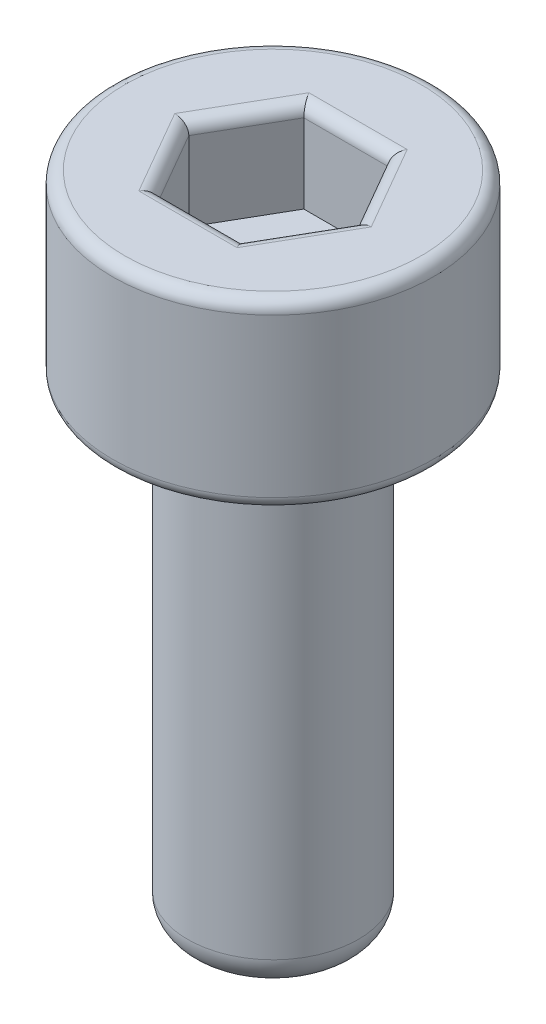
SolidWorks part; units mm, degrees
ref_plane "Front Plane" through (0, 0, 0) normal (0, 0, 1) x (1, 0, 0)
ref_plane "Top Plane" through (0, 0, 0) normal (0, 1, 0) x (1, 0, 0)
ref_plane "Right Plane" through (0, 0, 0) normal (1, 0, 0) x (0, 0, -1)
sketch "Sketch1" plane through (0, 0, 0) normal (0, 1, 0) x (1, 0, 0)
  circle A0 centre (0, 0) radius 2.64
  dimension "D1" = 5.28
extrude "Boss-Extrude1" add sketch "Sketch1" along normal blind 3
sketch "Sketch2" plane through (0, 0, 0) normal (0, -1, 0) x (1, 0, 0)
  circle A0 centre (0, 0) radius 1.405
  dimension "D1" = 2.81
extrude "Boss-Extrude2" add sketch "Sketch2" along normal blind 7.76
fillet "Fillet1" radius 0.2 2 edges at (0, 3, 2.64) (0, 0, 2.64)
sketch "Sketch3" plane through (0, 3, 0) normal (0, 1, 0) x (1, 0, 0)
  line L1 (1.3856, 0) -> (0.6928, 1.2)
  line L2 (0.6928, 1.2) -> (-0.6928, 1.2)
  line L3 (-0.6928, 1.2) -> (-1.3856, 0)
  line L4 (-1.3856, 0) -> (-0.6928, -1.2)
  line L5 (-0.6928, -1.2) -> (0.6928, -1.2)
  line L6 (0.6928, -1.2) -> (1.3856, 0)
  circle A0 centre (0, 0) radius 1.2 construction
  dimension "D1" = 2.4
extrude "Cut-Extrude1" cut sketch "Sketch3" against normal blind 1.5
fillet "Fillet2" radius 0.2 6 edges at (1.0392, 3, -0.6) (0, 3, -1.2) (-1.0392, 3, -0.6) (-1.0392, 3, 0.6) (0, 3, 1.2) (1.0392, 3, 0.6)
fillet "Fillet3" radius 0.5 1 edges at (0, -7.76, -1.405)
